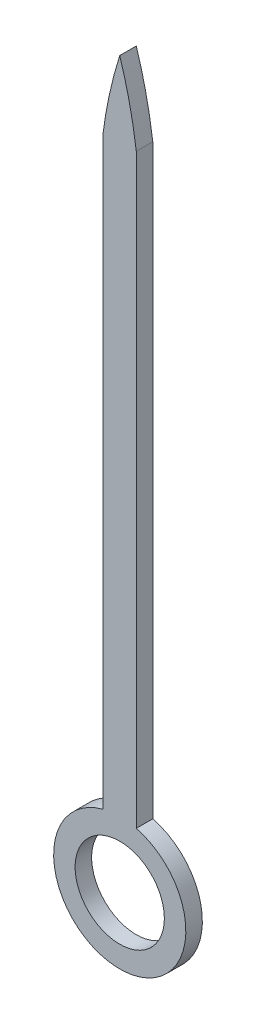
SolidWorks part; units mm, degrees
ref_plane "Front Plane" through (0, 0, 0) normal (0, 0, 1) x (1, 0, 0)
ref_plane "Top Plane" through (0, 0, 0) normal (0, 1, 0) x (1, 0, 0)
ref_plane "Right Plane" through (0, 0, 0) normal (1, 0, 0) x (0, 0, -1)
sketch "Sketch2" plane through (0, 0, 0) normal (0, 0, 1) x (1, 0, 0)
  line L0 (0, 0) -> (0, 64.284) construction
  line L3 (-1.5, 5.8095) -> (-1.5, 59.0371)
  line L5 (1.5, 5.8095) -> (1.5, 59.0371)
  line L6 (0, 65.8095) -> (0, 5.8095) construction
  line L7 (-1.5, 32.4233) -> (1.5, 32.4233) construction
  circle A0 centre (0, 0) radius 4.05
  arc A1 (-1.5, 5.8095) -> (1.5, 5.8095) centre (0, 0) ccw
  spline S0 degree 2 poles (0, 65.8095) (-1.0515, 62.4872) (-1.5, 59.0371) knots 0 0 0 1 1 1
  spline S1 degree 2 poles (0, 65.8095) (1.0515, 62.4872) (1.5, 59.0371) knots 0 0 0 1 1 1
  point P6 (1.0497, 61.752)
  point P333 (0, 32.4233)
  dimension "D1" = 8.1
  dimension "D2" = 12
  dimension "D3" = 60
  dimension "D4" = 3
  dimension "D5" = 65.8095
extrude "Boss-Extrude1" add sketch "Sketch2" along normal blind 1.5
